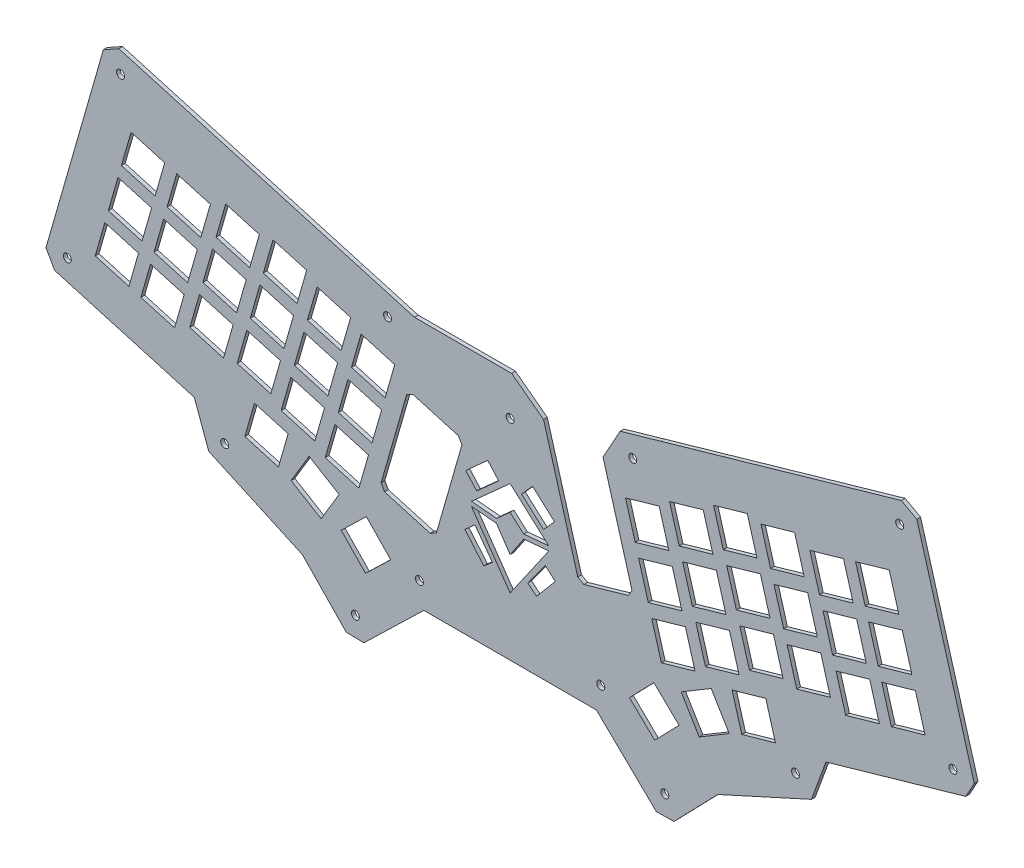
SolidWorks part; units mm, degrees
ref_plane "Plan de face" through (0, 0, 0) normal (0, 0, 1) x (1, 0, 0)
ref_plane "Plan de dessus" through (0, 0, 0) normal (0, 1, 0) x (1, 0, 0)
ref_plane "Plan de droite" through (0, 0, 0) normal (1, 0, 0) x (0, 0, -1)
sketch "Esquisse1" plane through (0, 0, 0) normal (0, 0, 1) x (1, 0, 0)
  line L0 (-121.6461, -32.0475) -> (-108.1875, -28.1884)
  line L1 (-108.1875, -28.1884) -> (-104.3283, -41.647)
  line L2 (-104.3283, -41.647) -> (-117.7869, -45.5062)
  line L3 (-117.7869, -45.5062) -> (-121.6461, -32.0475)
  line L4 (-100.1763, -37.9855) -> (-104.0355, -24.5269)
  line L5 (-104.0355, -24.5269) -> (-90.5769, -20.6677)
  line L6 (-90.5769, -20.6677) -> (-86.7177, -34.1263)
  line L7 (-86.7177, -34.1263) -> (-100.1763, -37.9855)
  line L8 (-82.5657, -30.4649) -> (-86.4249, -17.0063)
  line L9 (-86.4249, -17.0063) -> (-72.9663, -13.1471)
  line L10 (-72.9663, -13.1471) -> (-69.1071, -26.6057)
  line L11 (-69.1071, -26.6057) -> (-82.5657, -30.4649)
  line L12 (-63.6458, -27.5106) -> (-67.505, -14.0519)
  line L13 (-67.505, -14.0519) -> (-54.0463, -10.1927)
  line L14 (-54.0463, -10.1927) -> (-50.1872, -23.6514)
  line L15 (-50.1872, -23.6514) -> (-63.6458, -27.5106)
  line L16 (-44.0711, -26.8394) -> (-47.9303, -13.3808)
  line L17 (-47.9303, -13.3808) -> (-34.4717, -9.5216)
  line L18 (-34.4717, -9.5216) -> (-30.6125, -22.9802)
  line L19 (-30.6125, -22.9802) -> (-44.0711, -26.8394)
  line L20 (-25.8054, -21.6018) -> (-29.6646, -8.1432)
  line L21 (-29.6646, -8.1432) -> (-16.206, -4.284)
  line L22 (-16.206, -4.284) -> (-12.3468, -17.7426)
  line L23 (-12.3468, -17.7426) -> (-25.8054, -21.6018)
  line L24 (-116.4086, -50.3128) -> (-102.95, -46.4536)
  line L25 (-102.95, -46.4536) -> (-99.0908, -59.9122)
  line L26 (-99.0908, -59.9122) -> (-112.5494, -63.7714)
  line L27 (-112.5494, -63.7714) -> (-116.4086, -50.3128)
  line L28 (-98.798, -42.7922) -> (-85.3394, -38.933)
  line L29 (-85.3394, -38.933) -> (-81.4802, -52.3916)
  line L30 (-81.4802, -52.3916) -> (-94.9388, -56.2508)
  line L31 (-94.9388, -56.2508) -> (-98.798, -42.7922)
  line L32 (-81.1874, -35.2715) -> (-67.7288, -31.4123)
  line L33 (-67.7288, -31.4123) -> (-63.8696, -44.8709)
  line L34 (-63.8696, -44.8709) -> (-77.3282, -48.7301)
  line L35 (-77.3282, -48.7301) -> (-81.1874, -35.2715)
  line L36 (-62.2675, -32.3172) -> (-48.8089, -28.458)
  line L37 (-48.8089, -28.458) -> (-44.9497, -41.9166)
  line L38 (-44.9497, -41.9166) -> (-58.4083, -45.7758)
  line L39 (-58.4083, -45.7758) -> (-62.2675, -32.3172)
  line L40 (-42.6928, -31.646) -> (-29.2342, -27.7869)
  line L41 (-29.2342, -27.7869) -> (-25.375, -41.2455)
  line L42 (-25.375, -41.2455) -> (-38.8336, -45.1047)
  line L43 (-38.8336, -45.1047) -> (-42.6928, -31.646)
  line L44 (-24.4271, -26.4084) -> (-10.9685, -22.5492)
  line L45 (-10.9685, -22.5492) -> (-7.1093, -36.0078)
  line L46 (-7.1093, -36.0078) -> (-20.5679, -39.867)
  line L47 (-20.5679, -39.867) -> (-24.4271, -26.4084)
  line L48 (-19.1896, -44.6737) -> (-5.731, -40.8145)
  line L49 (-5.731, -40.8145) -> (-1.8718, -54.2731)
  line L50 (-1.8718, -54.2731) -> (-15.3304, -58.1323)
  line L51 (-15.3304, -58.1323) -> (-19.1896, -44.6737)
  line L52 (-37.4554, -49.9113) -> (-23.9967, -46.0521)
  line L53 (-23.9967, -46.0521) -> (-20.1376, -59.5107)
  line L54 (-20.1376, -59.5107) -> (-33.5962, -63.3699)
  line L55 (-33.5962, -63.3699) -> (-37.4554, -49.9113)
  line L56 (-57.03, -50.5825) -> (-43.5714, -46.7233)
  line L57 (-43.5714, -46.7233) -> (-39.7122, -60.1819)
  line L58 (-39.7122, -60.1819) -> (-53.1708, -64.0411)
  line L59 (-53.1708, -64.0411) -> (-57.03, -50.5825)
  line L60 (-75.9499, -53.5368) -> (-62.4913, -49.6776)
  line L61 (-62.4913, -49.6776) -> (-58.6321, -63.1362)
  line L62 (-58.6321, -63.1362) -> (-72.0908, -66.9954)
  line L63 (-72.0908, -66.9954) -> (-75.9499, -53.5368)
  line L64 (-93.5605, -61.0574) -> (-80.1019, -57.1982)
  line L65 (-80.1019, -57.1982) -> (-76.2427, -70.6569)
  line L66 (-76.2427, -70.6569) -> (-89.7013, -74.516)
  line L67 (-89.7013, -74.516) -> (-93.5605, -61.0574)
  line L68 (-111.1711, -68.5781) -> (-97.7125, -64.7189)
  line L69 (-97.7125, -64.7189) -> (-93.8533, -78.1775)
  line L70 (-93.8533, -78.1775) -> (-107.3119, -82.0367)
  line L71 (-107.3119, -82.0367) -> (-111.1711, -68.5781)
  line L72 (-79.0181, -77.3048) -> (-65.5595, -73.4456)
  line L73 (-65.5595, -73.4456) -> (-61.7003, -86.9042)
  line L74 (-61.7003, -86.9042) -> (-75.1589, -90.7634)
  line L75 (-75.1589, -90.7634) -> (-79.0181, -77.3048)
  line L76 (-99.4001, -88.1351) -> (-87.3916, -80.9362)
  line L77 (-87.3916, -80.9362) -> (-80.1927, -92.9448)
  line L78 (-80.1927, -92.9448) -> (-92.2012, -100.1436)
  line L79 (-92.2012, -100.1436) -> (-99.4001, -88.1351)
  line L80 (-120.0498, -100.4367) -> (-110.317, -90.3719)
  line L81 (-110.317, -90.3719) -> (-100.2522, -100.1047)
  line L82 (-100.2522, -100.1047) -> (-109.985, -110.1695)
  line L83 (-109.985, -110.1695) -> (-120.0498, -100.4367)
  line L86 (0.634, -55.7756) -> (-52.9527, -71.1413) construction
  line L89 (-59.2205, -88.2424) -> (-52.9527, -71.1413) construction
  line L96 (-93.4066, -103.0586) -> (-59.4637, -88.3612) construction
  line L97 (-105.418, -115.2057) -> (-93.9754, -103.3509) construction
  line L98 (-126.5332, -96.9919) -> (-107.5003, -115.385) construction
  line L99 (-167.7972, -50.1766) -> (-183.2082, -64.014)
  line L100 (-106.3822, -25.4572) -> (-123.6848, -30.4187) construction
  line L101 (-72.1178, -10.6906) -> (-88.4663, -15.3784) construction
  line L102 (-53.2337, -7.6163) -> (-70.5393, -12.5786) construction
  line L103 (-33.6604, -6.9452) -> (-50.9661, -11.9075) construction
  line L104 (-15.3965, -1.7081) -> (-31.745, -6.396) construction
  line L105 (0.5403, -55.2132) -> (-14.6896, -2.0999) construction
  line L106 (-16.199, -60.6113) -> (0.1495, -55.9235) construction
  line L107 (-52.7198, -71.0835) -> (-18.1144, -61.1606) construction
  line L108 (-59.1184, -88.0534) -> (-52.9674, -71.2752) construction
  line L109 (-183.2082, -64.014) -> (-173.1824, -64.9357)
  line L113 (-102.2678, -134.438) -> (-84.7238, -116.3191)
  line L114 (-84.7238, -116.3191) -> (-47.2969, -99.2981)
  line L115 (-47.2969, -99.2981) -> (-41.4917, -83.4594)
  line L116 (14.3812, -67.4381) -> (-41.4917, -83.4594)
  line L117 (17.8093, -61.2536) -> (-5.1371, 18.7701)
  line L122 (-11.3217, 22.1985) -> (-107.4545, -5.3614)
  line L129 (-167.7953, -27.6055) -> (-167.7953, -64.7189) construction
  line L130 (-242.0685, -103.8419) -> (-276.37, -88.2424) construction
  line L131 (-229.5108, -116.8112) -> (-242.0685, -103.8419) construction
  line L138 (-208.9328, -96.8551) -> (-229.5108, -116.8112) construction
  line L139 (-225.5107, -79.6567) -> (-208.9328, -96.8551) construction
  line L140 (-109.3352, -134.5492) -> (-102.2678, -134.438)
  line L142 (-5.1371, 18.7701) -> (-11.3217, 22.1985)
  line L143 (-211.4691, -30.6868) -> (-225.5107, -79.6567) construction
  line L147 (-114.18, -7.2899) -> (-107.4545, -5.3614)
  line L148 (-114.18, -7.2899) -> (-123.7936, -10.0465)
  line L154 (-4.3102, 15.8863) -> (-127.3606, -19.3904) construction
  line L155 (-131.531, -101.8802) -> (-105.9239, -126.7133) construction
  line L156 (-105.9239, -126.7133) -> (-89.4162, -109.6646) construction
  line L157 (-127.3539, -97.573) -> (-106.0575, -118.2258) construction
  line L158 (-106.0575, -118.2258) -> (-92.9354, -104.6737) construction
  line L159 (-92.9354, -104.6737) -> (-58.4256, -88.9794) construction
  line L160 (-58.4256, -88.9794) -> (-52.1886, -71.9625) construction
  line L161 (1.8709, -56.4612) -> (-52.1886, -71.9625) construction
  line L162 (1.8709, -56.4612) -> (-14.1861, -0.4639) construction
  line L163 (-14.1861, -0.4639) -> (-50.7166, -10.9388) construction
  line L164 (-50.7166, -10.9388) -> (-52.026, -6.3725) construction
  line L165 (-52.026, -6.3725) -> (-70.2913, -11.61) construction
  line L166 (-70.2913, -11.61) -> (-70.911, -9.4488) construction
  line L167 (-70.911, -9.4488) -> (-90.1377, -14.9608) construction
  line L168 (-90.1377, -14.9608) -> (-89.5177, -17.1231) construction
  line L169 (-89.5177, -17.1231) -> (-107.783, -22.3606) construction
  line L170 (-107.783, -22.3606) -> (-107.0938, -24.7639) construction
  line L171 (-107.0938, -24.7639) -> (-125.3583, -30.0011) construction
  line L172 (-125.3583, -30.0011) -> (-111.0411, -79.9324) construction
  line L173 (-110.7998, -78.9627) -> (-127.3777, -96.1611) construction
  line L174 (-89.4162, -109.6646) -> (-53.6562, -93.4017) construction
  line L175 (-53.6562, -93.4017) -> (-47.6042, -76.8897) construction
  line L176 (9.2923, -60.5749) -> (-47.6042, -76.8897) construction
  line L177 (9.2923, -60.5749) -> (-12.0005, 13.6817) construction
  line L178 (-229.7336, -25.4495) -> (-211.4691, -30.6868) construction
  line L179 (-229.0444, -23.0462) -> (-229.7336, -25.4495) construction
  line L180 (-173.1824, -64.9357) -> (-167.7972, -60.1004)
  line L181 (-247.3097, -17.8087) -> (-229.0444, -23.0462) construction
  line L185 (17.8093, -61.2536) -> (14.3812, -67.4381)
  line L186 (-183.2987, -65.7677) -> (-173.2729, -66.6895)
  line L187 (-173.2729, -66.6895) -> (-167.8052, -74.7882)
  line L190 (-246.6897, -15.6465) -> (-247.3097, -17.8087) construction
  line L191 (-263.9939, -10.6857) -> (-246.6897, -15.6465) construction
  line L192 (-264.6136, -12.8469) -> (-263.9939, -10.6857) construction
  line L193 (-282.8789, -7.6094) -> (-264.6136, -12.8469) construction
  line L194 (-284.1883, -12.1757) -> (-282.8789, -7.6094) construction
  line L195 (-320.7188, -1.7008) -> (-284.1883, -12.1757) construction
  line L196 (-336.2245, -55.7756) -> (-320.7188, -1.7008) construction
  line L197 (-183.2987, -65.7677) -> (-167.8052, -88.0782)
  line L198 (-181.8414, -71.5322) -> (-174.8684, -81.0171)
  line L199 (-174.8684, -81.0171) -> (-178.3549, -83.9622)
  line L200 (-344.8828, -60.5749) -> (-323.5901, 13.6817) construction
  line L201 (-344.8828, -60.5749) -> (-287.9863, -76.8897) construction
  line L202 (-281.9343, -93.4017) -> (-287.9863, -76.8897) construction
  line L203 (-246.1743, -109.6646) -> (-281.9343, -93.4017) construction
  line L204 (-224.7907, -78.9627) -> (-208.2128, -96.1611) construction
  line L205 (-210.2322, -30.0011) -> (-224.5494, -79.9324) construction
  line L206 (-228.4967, -24.7639) -> (-210.2322, -30.0011) construction
  line L207 (-227.8075, -22.3606) -> (-228.4967, -24.7639) construction
  line L208 (-246.0728, -17.1231) -> (-227.8075, -22.3606) construction
  line L209 (-245.4528, -14.9608) -> (-246.0728, -17.1231) construction
  line L210 (-264.6796, -9.4488) -> (-245.4528, -14.9608) construction
  line L211 (-265.2993, -11.61) -> (-264.6796, -9.4488) construction
  line L212 (-283.5645, -6.3725) -> (-265.2993, -11.61) construction
  line L213 (-284.8739, -10.9388) -> (-283.5645, -6.3725) construction
  line L217 (0.634, -55.7756) -> (-14.8717, -1.7008) construction
  line L220 (-14.8717, -1.7008) -> (-51.4022, -12.1757) construction
  line L221 (-51.4022, -12.1757) -> (-52.7116, -7.6094) construction
  line L222 (-52.7116, -7.6094) -> (-70.9769, -12.8469) construction
  line L223 (-70.9769, -12.8469) -> (-71.5966, -10.6857) construction
  line L224 (-71.5966, -10.6857) -> (-88.9008, -15.6465) construction
  line L225 (-88.9008, -15.6465) -> (-88.2808, -17.8087) construction
  line L226 (-88.2808, -17.8087) -> (-106.5461, -23.0462) construction
  line L227 (-106.5461, -23.0462) -> (-105.8569, -25.4495) construction
  line L228 (-105.8569, -25.4495) -> (-124.1214, -30.6868) construction
  line L231 (-124.1214, -30.6868) -> (-110.0799, -79.6567) construction
  line L232 (-110.0799, -79.6567) -> (-126.6577, -96.8551) construction
  line L233 (-126.6577, -96.8551) -> (-106.0797, -116.8112) construction
  line L234 (-106.0797, -116.8112) -> (-93.522, -103.8419) construction
  line L235 (-93.522, -103.8419) -> (-59.2205, -88.2424) construction
  line L236 (-321.4044, -0.4639) -> (-284.8739, -10.9388) construction
  line L237 (-337.4614, -56.4612) -> (-321.4044, -0.4639) construction
  line L238 (-337.4614, -56.4612) -> (-283.4019, -71.9625) construction
  line L239 (-277.1649, -88.9794) -> (-283.4019, -71.9625) construction
  line L240 (-242.6551, -104.6737) -> (-277.1649, -88.9794) construction
  line L241 (-229.5331, -118.2258) -> (-242.6551, -104.6737) construction
  line L242 (-208.2366, -97.573) -> (-229.5331, -118.2258) construction
  line L243 (-229.6666, -126.7133) -> (-246.1743, -109.6646) construction
  line L244 (-204.0596, -101.8802) -> (-229.6666, -126.7133) construction
  line L245 (-331.2803, 15.8863) -> (-208.2299, -19.3904) construction
  line L246 (-178.3549, -83.9622) -> (-185.8788, -75.0552)
  line L247 (-185.8788, -75.0552) -> (-181.8414, -71.5322)
  line L248 (-176.7625, -46.6332) -> (-185.5498, -54.5291)
  line L249 (-185.5498, -54.5291) -> (-181.1562, -59.4188)
  line L250 (-181.1562, -59.4188) -> (-172.3689, -51.5229)
  line L251 (-276.4721, -88.0534) -> (-282.6232, -71.2752) construction
  line L252 (-282.8707, -71.0835) -> (-317.4761, -61.1606) construction
  line L253 (-319.3915, -60.6113) -> (-335.74, -55.9235) construction
  line L254 (-336.1309, -55.2132) -> (-320.9009, -2.0999) construction
  line L255 (-320.194, -1.7081) -> (-303.8455, -6.396) construction
  line L256 (-301.9301, -6.9452) -> (-284.6245, -11.9075) construction
  line L257 (-282.3568, -7.6163) -> (-265.0512, -12.5786) construction
  line L258 (-263.4727, -10.6906) -> (-247.1242, -15.3784) construction
  line L259 (-229.2083, -25.4572) -> (-211.9057, -30.4187) construction
  line L260 (-172.3689, -51.5229) -> (-176.7625, -46.6332)
  line L261 (-209.0573, -96.9919) -> (-228.0902, -115.385) construction
  line L262 (-230.1725, -115.2057) -> (-241.6151, -103.3509) construction
  line L263 (-242.1839, -103.0586) -> (-276.1268, -88.3612) construction
  line L264 (-276.37, -88.2424) -> (-282.6379, -71.1413) construction
  line L265 (-336.2245, -55.7756) -> (-282.6379, -71.1413) construction
  line L268 (-353.3998, -61.2536) -> (-349.9717, -67.4381)
  line L274 (-221.4105, -7.2899) -> (-206.0252, -11.7015)
  line L275 (-221.4105, -7.2899) -> (-228.136, -5.3614)
  line L276 (-330.4534, 18.7701) -> (-324.2688, 22.1985)
  line L277 (-226.2553, -134.5492) -> (-233.3227, -134.438)
  line L281 (-324.2688, 22.1985) -> (-228.136, -5.3614)
  line L282 (-353.3998, -61.2536) -> (-330.4534, 18.7701)
  line L283 (-349.9717, -67.4381) -> (-294.0988, -83.4594)
  line L284 (-288.2936, -99.2981) -> (-294.0988, -83.4594)
  line L285 (-250.8667, -116.3191) -> (-288.2936, -99.2981)
  line L286 (-233.3227, -134.438) -> (-250.8667, -116.3191)
  line L288 (-225.6055, -110.1695) -> (-215.5407, -100.4367)
  line L289 (-235.3383, -100.1047) -> (-225.6055, -110.1695)
  line L290 (-225.2735, -90.3719) -> (-235.3383, -100.1047)
  line L291 (-215.5407, -100.4367) -> (-225.2735, -90.3719)
  line L292 (-243.3893, -100.1436) -> (-236.1904, -88.1351)
  line L293 (-255.3978, -92.9448) -> (-243.3893, -100.1436)
  line L294 (-248.1989, -80.9362) -> (-255.3978, -92.9448)
  line L295 (-236.1904, -88.1351) -> (-248.1989, -80.9362)
  line L296 (-260.4316, -90.7634) -> (-256.5724, -77.3048)
  line L297 (-273.8902, -86.9042) -> (-260.4316, -90.7634)
  line L298 (-270.031, -73.4456) -> (-273.8902, -86.9042)
  line L299 (-256.5724, -77.3048) -> (-270.031, -73.4456)
  line L300 (-228.2786, -82.0367) -> (-224.4194, -68.5781)
  line L301 (-241.7372, -78.1775) -> (-228.2786, -82.0367)
  line L302 (-237.878, -64.7189) -> (-241.7372, -78.1775)
  line L303 (-224.4194, -68.5781) -> (-237.878, -64.7189)
  line L304 (-245.8892, -74.516) -> (-242.03, -61.0574)
  line L305 (-259.3478, -70.6569) -> (-245.8892, -74.516)
  line L306 (-255.4886, -57.1982) -> (-259.3478, -70.6569)
  line L307 (-242.03, -61.0574) -> (-255.4886, -57.1982)
  line L308 (-263.4998, -66.9954) -> (-259.6406, -53.5368)
  line L309 (-276.9584, -63.1362) -> (-263.4998, -66.9954)
  line L310 (-273.0992, -49.6776) -> (-276.9584, -63.1362)
  line L311 (-259.6406, -53.5368) -> (-273.0992, -49.6776)
  line L312 (-282.4197, -64.0411) -> (-278.5605, -50.5825)
  line L313 (-295.8783, -60.1819) -> (-282.4197, -64.0411)
  line L314 (-292.0191, -46.7233) -> (-295.8783, -60.1819)
  line L315 (-278.5605, -50.5825) -> (-292.0191, -46.7233)
  line L316 (-301.9944, -63.3699) -> (-298.1352, -49.9113)
  line L317 (-315.453, -59.5107) -> (-301.9944, -63.3699)
  line L318 (-311.5938, -46.0521) -> (-315.453, -59.5107)
  line L319 (-298.1352, -49.9113) -> (-311.5938, -46.0521)
  line L320 (-320.2601, -58.1323) -> (-316.4009, -44.6737)
  line L321 (-333.7187, -54.2731) -> (-320.2601, -58.1323)
  line L322 (-329.8595, -40.8145) -> (-333.7187, -54.2731)
  line L323 (-316.4009, -44.6737) -> (-329.8595, -40.8145)
  line L324 (-315.0226, -39.867) -> (-311.1634, -26.4084)
  line L325 (-328.4812, -36.0078) -> (-315.0226, -39.867)
  line L326 (-324.622, -22.5492) -> (-328.4812, -36.0078)
  line L327 (-311.1634, -26.4084) -> (-324.622, -22.5492)
  line L328 (-296.7569, -45.1047) -> (-292.8977, -31.646)
  line L329 (-310.2155, -41.2455) -> (-296.7569, -45.1047)
  line L330 (-306.3563, -27.7869) -> (-310.2155, -41.2455)
  line L331 (-292.8977, -31.646) -> (-306.3563, -27.7869)
  line L332 (-277.1822, -45.7758) -> (-273.323, -32.3172)
  line L333 (-290.6408, -41.9166) -> (-277.1822, -45.7758)
  line L334 (-286.7817, -28.458) -> (-290.6408, -41.9166)
  line L335 (-273.323, -32.3172) -> (-286.7817, -28.458)
  line L336 (-258.2623, -48.7301) -> (-254.4031, -35.2715)
  line L337 (-271.7209, -44.8709) -> (-258.2623, -48.7301)
  line L338 (-267.8617, -31.4123) -> (-271.7209, -44.8709)
  line L339 (-254.4031, -35.2715) -> (-267.8617, -31.4123)
  line L340 (-240.6517, -56.2508) -> (-236.7925, -42.7922)
  line L341 (-254.1103, -52.3916) -> (-240.6517, -56.2508)
  line L342 (-250.2511, -38.933) -> (-254.1103, -52.3916)
  line L343 (-236.7925, -42.7922) -> (-250.2511, -38.933)
  line L344 (-223.0411, -63.7714) -> (-219.1819, -50.3128)
  line L345 (-236.4997, -59.9122) -> (-223.0411, -63.7714)
  line L346 (-232.6405, -46.4536) -> (-236.4997, -59.9122)
  line L347 (-219.1819, -50.3128) -> (-232.6405, -46.4536)
  line L348 (-323.2438, -17.7426) -> (-309.7851, -21.6018)
  line L349 (-319.3846, -4.284) -> (-323.2438, -17.7426)
  line L350 (-305.926, -8.1432) -> (-319.3846, -4.284)
  line L351 (-309.7851, -21.6018) -> (-305.926, -8.1432)
  line L352 (-304.978, -22.9802) -> (-291.5194, -26.8394)
  line L353 (-301.1188, -9.5216) -> (-304.978, -22.9802)
  line L354 (-287.6602, -13.3808) -> (-301.1188, -9.5216)
  line L355 (-291.5194, -26.8394) -> (-287.6602, -13.3808)
  line L356 (-285.4034, -23.6514) -> (-271.9448, -27.5106)
  line L357 (-281.5442, -10.1927) -> (-285.4034, -23.6514)
  line L358 (-268.0856, -14.0519) -> (-281.5442, -10.1927)
  line L359 (-271.9448, -27.5106) -> (-268.0856, -14.0519)
  line L360 (-266.4834, -26.6057) -> (-253.0248, -30.4649)
  line L361 (-262.6242, -13.1471) -> (-266.4834, -26.6057)
  line L362 (-249.1656, -17.0063) -> (-262.6242, -13.1471)
  line L363 (-253.0248, -30.4649) -> (-249.1656, -17.0063)
  line L364 (-248.8728, -34.1263) -> (-235.4142, -37.9855)
  line L365 (-245.0136, -20.6677) -> (-248.8728, -34.1263)
  line L366 (-231.555, -24.5269) -> (-245.0136, -20.6677)
  line L367 (-235.4142, -37.9855) -> (-231.555, -24.5269)
  line L368 (-217.8036, -45.5062) -> (-213.9444, -32.0475)
  line L369 (-231.2622, -41.647) -> (-217.8036, -45.5062)
  line L370 (-227.4031, -28.1884) -> (-231.2622, -41.647)
  line L371 (-213.9444, -32.0475) -> (-227.4031, -28.1884)
  line L372 (-226.2553, -134.5492) -> (-202.2968, -111.3509)
  line L373 (-109.3352, -134.5492) -> (-133.2937, -111.3509)
  line L374 (-141.5559, -103.3509) -> (-194.0347, -103.3509) construction
  line L375 (-167.7972, -50.1766) -> (-152.3861, -64.014)
  line L376 (-162.4119, -64.9357) -> (-167.7972, -60.1004)
  line L377 (-162.3376, -66.6895) -> (-167.8052, -74.7882)
  line L378 (-152.3118, -65.7677) -> (-167.8052, -88.0782)
  line L379 (-163.2254, -51.5229) -> (-158.8318, -46.6332)
  line L380 (-154.4381, -59.4188) -> (-163.2254, -51.5229)
  line L381 (-150.0445, -54.5291) -> (-154.4381, -59.4188)
  line L382 (-158.8318, -46.6332) -> (-150.0445, -54.5291)
  line L383 (-149.7316, -75.0552) -> (-153.7691, -71.5322)
  line L384 (-157.2555, -83.9622) -> (-149.7316, -75.0552)
  line L385 (-160.742, -81.0171) -> (-157.2555, -83.9622)
  line L386 (-153.7691, -71.5322) -> (-160.742, -81.0171)
  line L387 (-152.3118, -65.7677) -> (-162.3376, -66.6895)
  line L388 (-152.3861, -64.014) -> (-162.4119, -64.9357)
  line L389 (-206.0252, -11.7015) -> (-129.5654, -11.7015) construction
  line L390 (-119.0708, -62.7964) -> (-130.6498, -22.4155)
  line L391 (-123.5545, -47.16) -> (-127.4136, -33.7014) construction
  line L392 (-120.442, -65.2702) -> (-138.2688, -70.3819)
  line L393 (-140.7426, -69.0107) -> (-154.4194, -21.3141)
  line L394 (-167.1758, -11.7015) -> (-206.0252, -11.7015)
  line L395 (-154.4194, -21.3141) -> (-167.1758, -11.7015)
  line L396 (-123.7936, -10.0465) -> (-130.6498, -22.4155)
  line L397 (-138.2688, -70.3819) -> (-140.7426, -69.0107)
  line L398 (-119.0708, -62.7964) -> (-120.442, -65.2702)
  line L399 (-129.5654, -11.7015) -> (-123.7936, -10.0465) construction
  line L400 (-133.2937, -111.3509) -> (-202.2968, -111.3509)
  line L401 (-141.5559, -111.3509) -> (-194.0347, -111.3509) construction
  line L402 (-197.2749, -82.0103) -> (-187.0783, -46.443)
  line L403 (-188.4497, -43.9693) -> (-206.714, -38.7332)
  line L404 (-219.3843, -75.6719) -> (-209.1877, -40.1046)
  line L405 (-199.7487, -83.3817) -> (-218.0129, -78.1456)
  line L406 (-206.714, -38.7332) -> (-209.1877, -40.1046)
  line L407 (-187.0783, -46.443) -> (-188.4497, -43.9693)
  line L408 (-199.7487, -83.3817) -> (-197.2749, -82.0103)
  line L409 (-218.0129, -78.1456) -> (-219.3843, -75.6719)
  line L410 (-192.1766, -64.2267) -> (-167.7953, -64.7189) construction
  circle A2 centre (-12.0005, 13.6817) radius 1.6
  circle A3 centre (-12.0005, 13.6817) radius 3 construction
  circle A4 centre (-118.7579, -16.9241) radius 1.6
  circle A5 centre (9.2923, -60.5749) radius 1.6
  circle A6 centre (-53.6562, -93.4017) radius 1.6
  circle A7 centre (-105.9239, -126.7133) radius 1.6
  circle A8 centre (-131.531, -101.8802) radius 1.6
  circle A10 centre (-147.4897, -45.973) radius 1.6 construction
  circle A11 centre (-323.5901, 13.6817) radius 3 construction
  circle A12 centre (-188.1008, -45.973) radius 1.6 construction
  circle A14 centre (-204.0596, -101.8802) radius 1.6
  circle A15 centre (-229.6666, -126.7133) radius 1.6
  circle A16 centre (-281.9343, -93.4017) radius 1.6
  circle A17 centre (-344.8828, -60.5749) radius 1.6
  circle A18 centre (-216.8326, -16.9241) radius 1.6
  circle A19 centre (-323.5901, 13.6817) radius 1.6
  circle A20 centre (-167.7953, -27.6055) radius 1.6
  point P138 (-167.7953, -27.6055)
  point P139 (-6.5153, 23.5764)
  point P150 (-169.1046, -23.0392)
  point P200 (19.1875, -66.0599)
  point P203 (-141.5228, -71.3355)
  point P204 (-141.5228, 1.5705)
  point P263 (-133.4062, -12.8029)
  point P264 (-118.5195, -64.7189)
  point P283 (-140.1914, -70.9332)
  point P284 (-157.1758, -11.7015)
  point P405 (-354.778, -66.0599)
  point P406 (-329.0752, 23.5764)
  point P420 (0, 0)
  dimension "D3" = 3.2
  dimension "D4" = 6
  dimension "D6" = 3.2
  dimension "D7" = 3.2
  dimension "D8" = 3.2
  dimension "D9" = 3.2
  dimension "D10" = 3.2
  dimension "D16" = 3.2
  dimension "D2" = 6
  dimension "D5" = 8
extrude "Boss.-Extru.1" add sketch "Esquisse1" along normal blind 1.5
